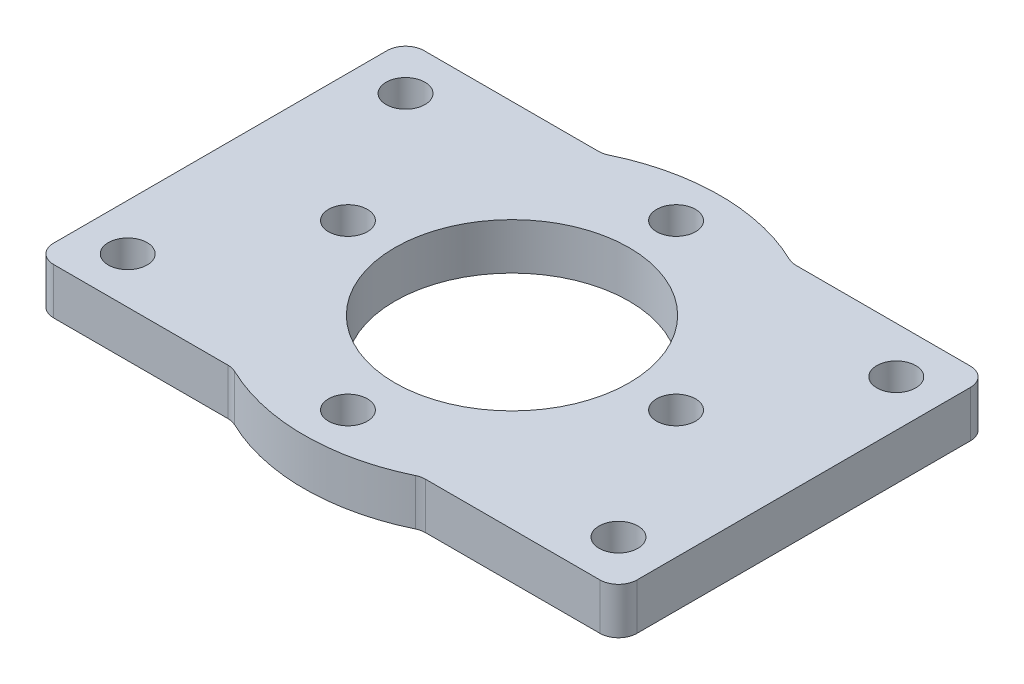
SolidWorks part; units mm, degrees
ref_plane "Front Plane" through (0, 0, 0) normal (0, 0, 1) x (1, 0, 0)
ref_plane "Top Plane" through (0, 0, 0) normal (0, 1, 0) x (1, 0, 0)
ref_plane "Right Plane" through (0, 0, 0) normal (1, 0, 0) x (0, 0, -1)
sketch "Sketch1" plane through (0, 0, 0) normal (0, 1, 0) x (1, 0, 0)
  line L0 (-12.9263, 25.4) -> (-40, 25.4)
  line L1 (40, 25.4) -> (12.9263, 25.4)
  line L2 (40, 25.4) -> (40, -25.4)
  line L3 (40, -25.4) -> (12.9263, -25.4)
  line L4 (-40, 25.4) -> (-40, -25.4)
  line L5 (40, 25.4) -> (-40, -25.4) construction
  line L6 (40, -25.4) -> (-40, 25.4) construction
  line L7 (-12.9263, -25.4) -> (-40, -25.4)
  arc A0 (12.9263, 25.4) -> (-12.9263, 25.4) centre (0, 0) ccw
  arc A1 (-12.9263, -25.4) -> (12.9263, -25.4) centre (0, 0) ccw
  point P7 (0, 0)
  dimension "D1" = 57
  dimension "D2" = 25.4
  dimension "D3" = 25.4
  dimension "D4" = 80
  dimension "D5" = 0
extrude "Boss-Extrude1" add sketch "Sketch1" along normal blind 6.35
sketch "Sketch2" plane through (0, 6.35, 0) normal (0, 1, 0) x (1, 0, 0)
  circle A0 centre (0, 0) radius 16.0655
  dimension "D1" = 32.131
extrude "Cut-Extrude1" cut sketch "Sketch2" against normal up to next
sketch "Sketch3" plane through (0, 6.35, 0) normal (0, 1, 0) x (1, 0, 0)
  circle A0 centre (0, 0) radius 22.5 construction
  circle A1 centre (0, 22.5) radius 2.665
  circle A2 centre (22.5, 0) radius 2.665
  circle A3 centre (0, -22.5) radius 2.665
  circle A4 centre (-22.5, 0) radius 2.665
  point P14 (0, 0)
  dimension "D1" = 45
  dimension "D2" = 5.33
  dimension "D3" = 4
extrude "Cut-Extrude2" cut sketch "Sketch3" against normal up to next
sketch "Sketch4" plane through (0, 6.35, 0) normal (0, 1, 0) x (1, 0, 0)
  line L0 (0, 28.5) -> (0, -28.5) construction
  line L1 (-40, -25.4) -> (-12.9263, -25.4) construction
  line L2 (-40, 25.4) -> (-40, -25.4) construction
  line L3 (-12.9263, 25.4) -> (-40, 25.4) construction
  circle A0 centre (-33.65, 19.05) radius 2.665
  circle A1 centre (-33.65, -19.05) radius 2.665
  arc A2 (12.9263, 25.4) -> (-12.9263, 25.4) centre (0, 0) ccw construction
  arc A3 (-12.9263, -25.4) -> (12.9263, -25.4) centre (0, 0) ccw construction
  circle A4 centre (33.65, 19.05) radius 2.665
  circle A5 centre (33.65, -19.05) radius 2.665
  dimension "D1" = 5.33
  dimension "D2" = 6.35
  dimension "D3" = 6.35
  dimension "D4" = 6.35
  dimension "D5" = 6.35
extrude "Cut-Extrude3" cut sketch "Sketch4" against normal up to next
fillet "Fillet1" radius 2.54 8 edges at (-40, 3.175, -25.4) (-12.9263, 3.175, -25.4) (12.9263, 3.175, -25.4) (40, 3.175, -25.4) (40, 3.175, 25.4) (12.9263, 3.175, 25.4) (-12.9263, 3.175, 25.4) (-40, 3.175, 25.4)
